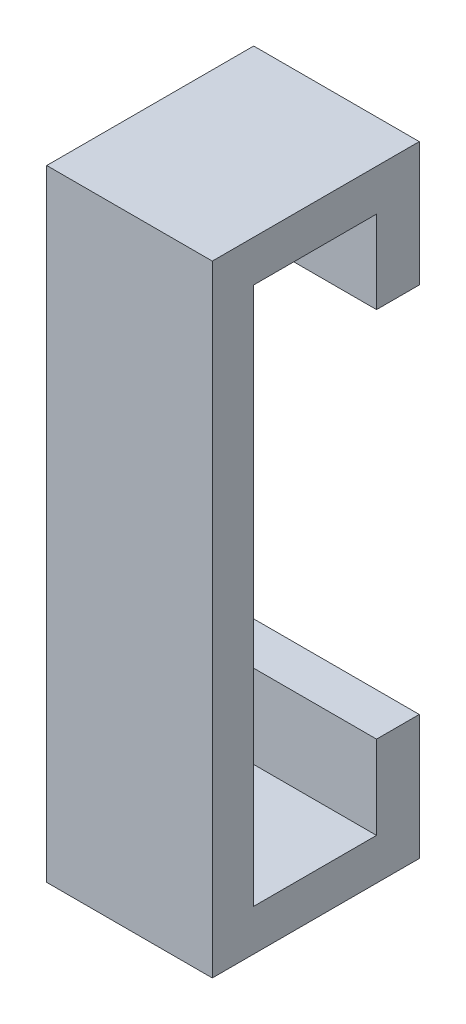
SolidWorks part; units mm, degrees
ref_plane "Front Plane" through (0, 0, 0) normal (1, 0, 0) x (0, 1, 0)
ref_plane "Top Plane" through (0, 0, 0) normal (0, 0, 1) x (0, 1, 0)
ref_plane "Right Plane" through (0, 0, 0) normal (0, 1, 0) x (-1, 0, 0)
sketch "Sketch1" plane through (0, 0, 0) normal (1, 0, 0) x (0, 1, 0)
  line L1 (0, 0) -> (38.1, 0)
  line L2 (0, 0) -> (0, 12.7)
  line L3 (0, 12.7) -> (38.1, 12.7)
  line L4 (38.1, 0) -> (38.1, 12.7)
  dimension "D1" = 38.1
  dimension "D2" = 12.7
extrude "Boss-Extrude1" add sketch "Sketch1" along normal blind 10.16
sketch "Sketch2" plane through (10.16, 0, 0) normal (1, 0, 0) x (0, 1, 0)
  line L0 (2.54, 10.16) -> (35.56, 10.16)
  line L1 (0, 12.7) -> (0, 0) construction
  line L2 (38.1, 12.7) -> (0, 12.7) construction
  line L3 (2.54, 10.16) -> (2.54, 2.6219)
  line L4 (35.56, 10.16) -> (35.56, 2.6219)
  line L5 (35.56, 2.6219) -> (30.48, 2.6219)
  line L6 (38.1, 0) -> (38.1, 12.7) construction
  line L8 (2.54, 2.6219) -> (7.6564, 2.6219)
  line L9 (7.6564, 2.6219) -> (7.6564, 0)
  line L10 (0, 0) -> (38.1, 0) construction
  line L11 (7.6564, 0) -> (30.48, 0)
  line L12 (30.48, 0) -> (30.48, 2.6219)
  dimension "D1" = 2.54
  dimension "D2" = 2.54
  dimension "D3" = 5.1164
  dimension "D4" = 5.08
  dimension "D5" = 2.54
extrude "Cut-Extrude1" cut sketch "Sketch2" against normal blind 10.16
